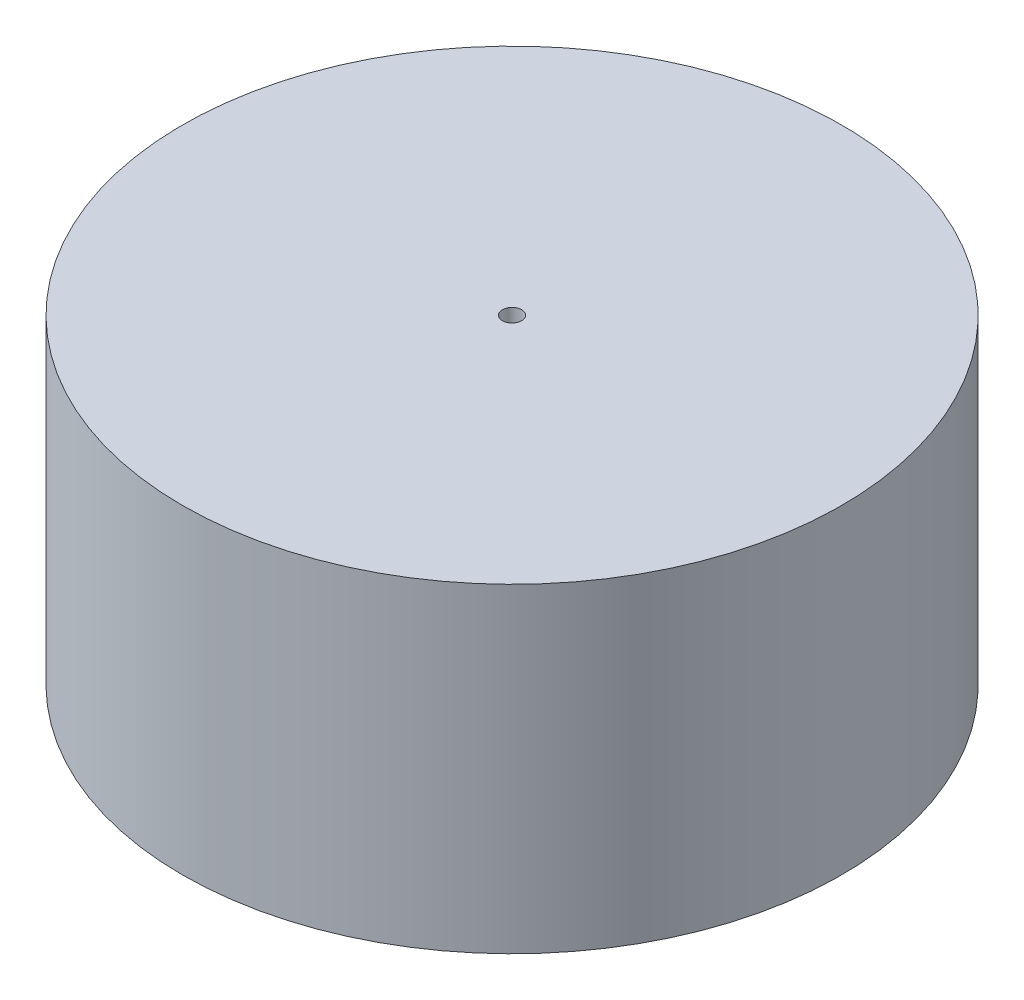
SolidWorks part; units mm, degrees
ref_plane "Front Plane" through (0, 0, 0) normal (0, 0, 1) x (1, 0, 0)
ref_plane "Top Plane" through (0, 0, 0) normal (0, 1, 0) x (1, 0, 0)
ref_plane "Right Plane" through (0, 0, 0) normal (1, 0, 0) x (0, 0, -1)
sketch "Sketch2" plane through (0, 0, 0) normal (0, 0, 1) x (1, 0, 0)
  line L0 (0, 28.7804) -> (0, -27.9337) construction
  line L1 (-37.26, 0.4233) -> (0.9, 0.4233) construction
  line L2 (0, 0.4233) -> (0.45, 0.4233) construction
  line L3 (0.45, 0.4233) -> (0.45, 15.4233)
  line L4 (0.45, 15.4233) -> (15.45, 15.4233)
  line L5 (15.45, 15.4233) -> (15.45, 0.4233)
  line L6 (15.45, 0.4233) -> (2.35, 0.4233)
  line L7 (0.45, 0.4233) -> (0.9, 0.4233) construction
  line L8 (0.9, 0.4233) -> (0.9, 11.2779)
  line L12 (14.4933, 9.04) -> (14.4933, 4.9773)
  line L13 (13.7881, 3.4075) -> (13.7325, 3.3581)
  line L14 (13.4896, 3.2384) -> (12.3421, 3.019)
  line L15 (11.307, 2.9209) -> (9.8174, 2.9209)
  line L16 (4.7781, 7.236) -> (4.1966, 10.9697)
  line L17 (4.3447, 10.0187) -> (4.4972, 9.04)
  line L18 (2.35, 0.4233) -> (2.35, 1.2067)
  line L19 (2.35, 1.2067) -> (2.329, 3.9031)
  line L20 (2.329, 3.9031) -> (2.329, 8.4309)
  line L23 (2.35, 0.4233) -> (50.4531, 0.4233) construction
  line L24 (0.9, 0.4233) -> (0.45, 0.4233)
  line L27 (4.3447, 10.0187) -> (4.1966, 10.9697)
  arc A2 (9.8174, 2.9209) -> (4.7781, 7.236) centre (9.8174, 8.0209) cw
  arc A3 (14.4933, 4.9773) -> (13.7881, 3.4075) centre (12.3933, 4.9773) cw
  arc A4 (13.4896, 3.2384) -> (13.7325, 3.3581) centre (13.3938, 3.7394) ccw
  arc A5 (11.307, 2.9209) -> (12.3421, 3.019) centre (11.307, 8.4309) ccw
  spline S0 degree 3 poles (0.9, 11.2779) (1.1543, 13.7967) (3.4127, 15.063) (6.3949, 13.6646) (6.379, 12.1274) (6.7767, 10.54) (6.742, 9.2216) (7.8257, 9.04) knots 0 0 0 0 0.440871 0.57776 0.724852 0.783369 1 1 1 1
  spline S1 degree 1 poles (7.8257, 9.04) (14.4933, 9.04) knots 0 0 1 1
  spline S2 degree 3 poles (4.1966, 10.9697) (3.9225, 11.4418) (2.509, 10.9908) (2.2205, 9.3304) (2.329, 8.4309) knots 0 0 0 0 0.262564 1 1 1 1
  point P10 (0, 0)
  point P12 (0.9, 11.6)
  point P15 (2.1416, 8.4309)
  point P21 (0, 0)
  point P25 (0, 0)
  point P26 (6.0784, 13.5155)
  point P28 (4.67, 14.3429)
  point P29 (0, 0)
  point P32 (0, 0)
  point P33 (0.9, 12.4233)
  point P42 (4.3456, 10.0131)
  dimension "D7" = 1.45
  dimension "D8" = 4.5278
  dimension "D9" = 5.1
  dimension "D10" = 2.1
  dimension "D11" = 0.51
  dimension "D12" = 5.51
  dimension "D2" = 15
  dimension "D3" = 15
  dimension "D4" = 0.45
  dimension "D5" = 12
  dimension "D6" = 0.45
revolve "Revolve1" add sketch "Sketch2" angle 360 about L0
